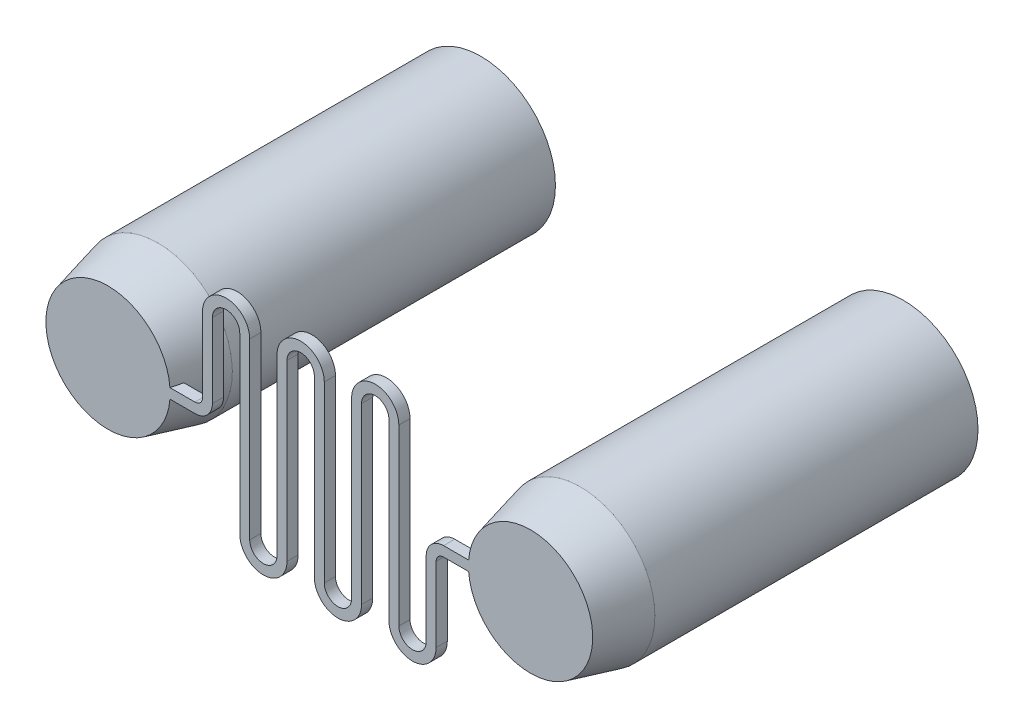
SolidWorks part; units mm, degrees
ref_plane "Front Plane" through (0, 0, 0) normal (0, 0, 1) x (1, 0, 0)
ref_plane "Top Plane" through (0, 0, 0) normal (0, 1, 0) x (1, 0, 0)
ref_plane "Right Plane" through (0, 0, 0) normal (1, 0, 0) x (0, 0, -1)
sketch "Sketch2" plane through (0, 0, 0) normal (0, 0, 1) x (1, 0, 0)
  line L3 (-20.5, -0.4) -> (-13.5, -0.4)
  line L6 (-12.1, 1) -> (-12.1, 7)
  line L9 (-9.9, 7) -> (-9.9, 0)
  line L12 (-9.9, 0) -> (-9.9, -7)
  line L15 (-6.1, -7) -> (-6.1, 0)
  line L18 (-6.1, 0) -> (-6.1, 7)
  line L21 (-3.9, 7) -> (-3.9, 0)
  line L22 (-3.9, 0) -> (-3.9, -7)
  line L23 (-0.1, -7) -> (-0.1, 0)
  line L24 (-0.1, 0) -> (-0.1, 7)
  line L25 (2.1, 7) -> (2.1, 0)
  line L26 (2.1, 0) -> (2.1, -7)
  line L27 (5.9, -7) -> (5.9, -1)
  line L28 (6.5, -0.4) -> (13.5, -0.4)
  line L29 (-20.5, 0.4) -> (-13.5, 0.4)
  line L30 (-12.9, 1) -> (-12.9, 7)
  line L31 (-9.1, 7) -> (-9.1, 0)
  line L32 (-9.1, 0) -> (-9.1, -7)
  line L33 (-6.9, -7) -> (-6.9, 0)
  line L34 (-6.9, 0) -> (-6.9, 7)
  line L35 (-3.1, 7) -> (-3.1, 0)
  line L36 (-3.1, 0) -> (-3.1, -7)
  line L37 (-0.9, -7) -> (-0.9, 0)
  line L38 (-0.9, 0) -> (-0.9, 7)
  line L39 (2.9, 7) -> (2.9, 0)
  line L40 (2.9, 0) -> (2.9, -7)
  line L41 (5.1, -7) -> (5.1, -1)
  line L42 (6.5, 0.4) -> (13.5, 0.4)
  arc A0 (-20.5, 0.4) -> (-20.5, -0.4) centre (-20.5, 0) ccw
  arc A1 (13.5, -0.4) -> (13.5, 0.4) centre (13.5, 0) ccw
  arc A8 (-12.1, 1) -> (-13.5, -0.4) centre (-13.5, 1) cw
  arc A9 (-12.1, 7) -> (-9.9, 7) centre (-11, 7) cw
  arc A10 (-9.9, -7) -> (-6.1, -7) centre (-8, -7) ccw
  arc A11 (-6.1, 7) -> (-3.9, 7) centre (-5, 7) cw
  arc A12 (-3.9, -7) -> (-0.1, -7) centre (-2, -7) ccw
  arc A13 (-0.1, 7) -> (2.1, 7) centre (1, 7) cw
  arc A14 (2.1, -7) -> (5.9, -7) centre (4, -7) ccw
  arc A15 (5.9, -1) -> (6.5, -0.4) centre (6.5, -1) cw
  arc A16 (-12.9, 1) -> (-13.5, 0.4) centre (-13.5, 1) cw
  arc A17 (-12.9, 7) -> (-9.1, 7) centre (-11, 7) cw
  arc A18 (-9.1, -7) -> (-6.9, -7) centre (-8, -7) ccw
  arc A19 (-6.9, 7) -> (-3.1, 7) centre (-5, 7) cw
  arc A20 (-3.1, -7) -> (-0.9, -7) centre (-2, -7) ccw
  arc A21 (-0.9, 7) -> (2.9, 7) centre (1, 7) cw
  arc A22 (2.9, -7) -> (5.1, -7) centre (4, -7) ccw
  arc A23 (5.1, -1) -> (6.5, 0.4) centre (6.5, -1) cw
  point P4 (0, 0)
  point P32 (5.5, 0)
  point P35 (-12.5, 0)
extrude "Boss-Extrude1" add sketch "Sketch2" along normal blind 0.9
ref_plane "Plane1" through (0, 0, 0) normal (0, 1, 0) x (1, 0, 0)
sketch "Sketch3" plane through (0, 0, 0) normal (0, 1, 0) x (1, 0, 0)
  line L0 (-20.5, -0.9) -> (-25.5, -0.9)
  line L2 (-20.5, -0.9) -> (-20.5, 29.1)
  line L3 (-20.5, 29.1) -> (-26.5, 29.1)
  line L4 (-26.5, 29.1) -> (-26.5, 3.1)
  line L6 (-26.5, 3.1) -> (-25.5, -0.9)
  dimension "D1" = 5
  dimension "D3" = 30
  dimension "D4" = 6
revolve "Revolve1" add sketch "Sketch3" angle 360 about L2
ref_plane "Plane2" through (0, 0, 0) normal (0, 1, 0) x (1, 0, 0)
sketch "Sketch4" plane through (0, 0, 0) normal (0, 1, 0) x (1, 0, 0)
  line L0 (13.5, -0.9) -> (18.5, -0.9)
  line L2 (13.5, -0.9) -> (13.5, 29.1)
  line L3 (13.5, 29.1) -> (19.5, 29.1)
  line L4 (19.5, 29.1) -> (19.5, 3.1)
  line L5 (19.5, 3.1) -> (18.5, -0.9)
  dimension "D1" = 30
  dimension "D2" = 5
  dimension "D4" = 6
revolve "Revolve2" add sketch "Sketch4" angle 360 about L2
